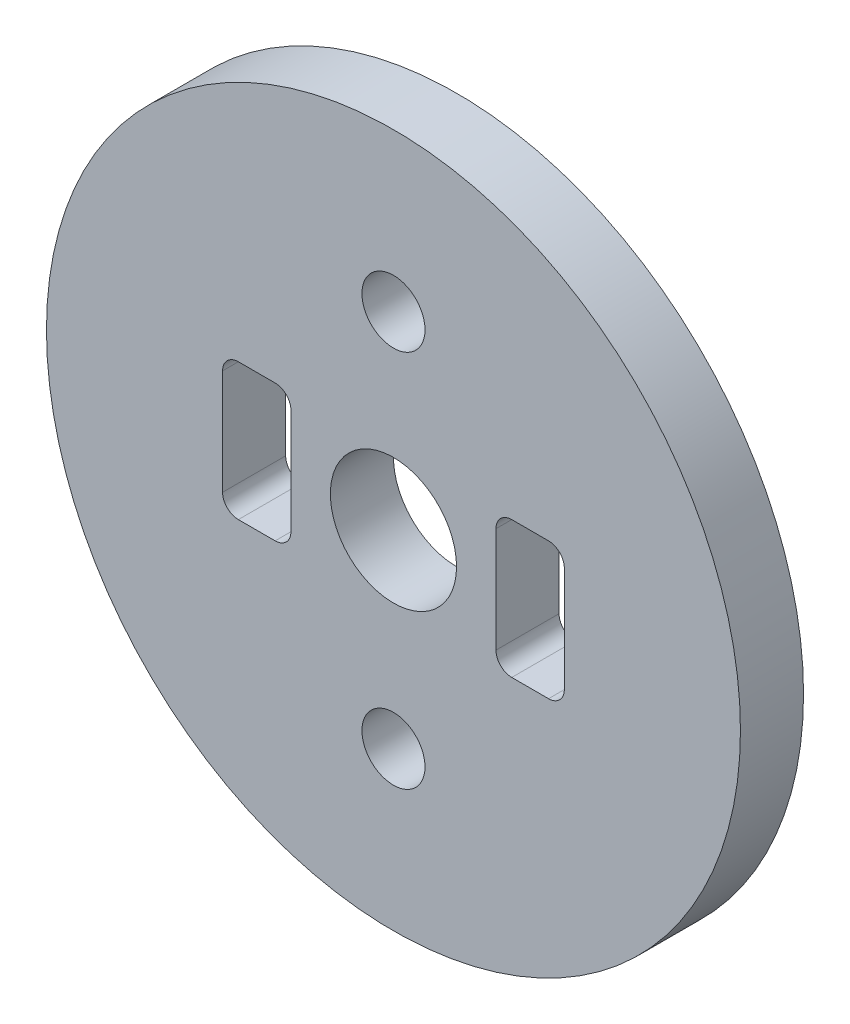
SolidWorks part; units mm, degrees
ref_plane "Alzado" through (0, 0, 0) normal (0, 0, 1) x (1, 0, 0)
ref_plane "Planta" through (0, 0, 0) normal (0, 1, 0) x (1, 0, 0)
ref_plane "Vista lateral" through (0, 0, 0) normal (1, 0, 0) x (0, 0, -1)
sketch "Model" plane through (0, 0, 0) normal (0, 0, 1) x (1, 0, 0)
  line L0 (223.1228, 245.202) -> (221.3728, 245.202)
  line L1 (223.8728, 239.452) -> (223.8728, 244.452)
  line L2 (221.3728, 238.702) -> (223.1228, 238.702)
  line L3 (220.6228, 244.452) -> (220.6228, 239.452)
  line L4 (208.3728, 245.202) -> (210.1228, 245.202)
  line L5 (207.6228, 239.452) -> (207.6228, 244.452)
  line L6 (210.1228, 238.702) -> (208.3728, 238.702)
  line L7 (210.8728, 244.452) -> (210.8728, 239.452)
  circle A0 centre (215.7478, 241.952) radius 3
  arc A1 (221.3728, 245.202) -> (220.6228, 244.452) centre (221.3728, 244.452) ccw
  arc A2 (223.8728, 244.452) -> (223.1228, 245.202) centre (223.1228, 244.452) ccw
  arc A3 (223.1228, 238.702) -> (223.8728, 239.452) centre (223.1228, 239.452) ccw
  arc A4 (220.6228, 239.452) -> (221.3728, 238.702) centre (221.3728, 239.452) ccw
  arc A5 (210.8728, 244.452) -> (210.1228, 245.202) centre (210.1228, 244.452) ccw
  arc A6 (208.3728, 245.202) -> (207.6228, 244.452) centre (208.3728, 244.452) ccw
  arc A7 (207.6228, 239.452) -> (208.3728, 238.702) centre (208.3728, 239.452) ccw
  arc A8 (210.1228, 238.702) -> (210.8728, 239.452) centre (210.1228, 239.452) ccw
  circle A9 centre (215.7478, 241.952) radius 16.5
  circle A10 centre (215.7478, 250.952) radius 1.5
  circle A11 centre (215.7478, 232.952) radius 1.5
extrude "Saliente-Extruir1" add sketch "Model" along normal blind 3
